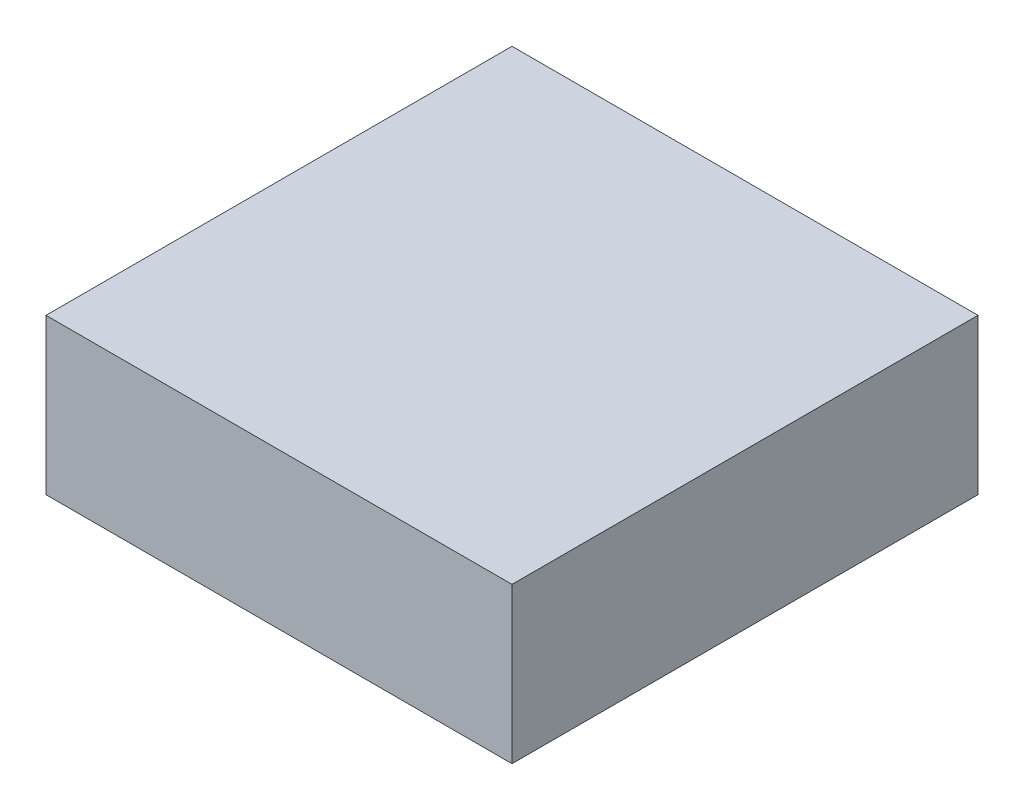
SolidWorks part; units mm, degrees
ref_plane "Front Plane" through (0, 0, 0) normal (0, 0, 1) x (1, 0, 0)
ref_plane "Top Plane" through (0, 0, 0) normal (0, 1, 0) x (1, 0, 0)
ref_plane "Right Plane" through (0, 0, 0) normal (1, 0, 0) x (0, 0, -1)
sketch "Sketch1" plane through (0, 0, 0) normal (0, 1, 0) x (1, 0, 0)
  line L1 (15, 15) -> (-15, 15)
  line L2 (15, 15) -> (15, -15)
  line L3 (15, -15) -> (-15, -15)
  line L4 (-15, 15) -> (-15, -15)
  line L5 (15, 15) -> (-15, -15) construction
  line L6 (15, -15) -> (-15, 15) construction
  point P0 (0, 0)
  dimension "D1" = 30
  dimension "D2" = 30
extrude "Boss-Extrude1" add sketch "Sketch1" along normal blind 10
